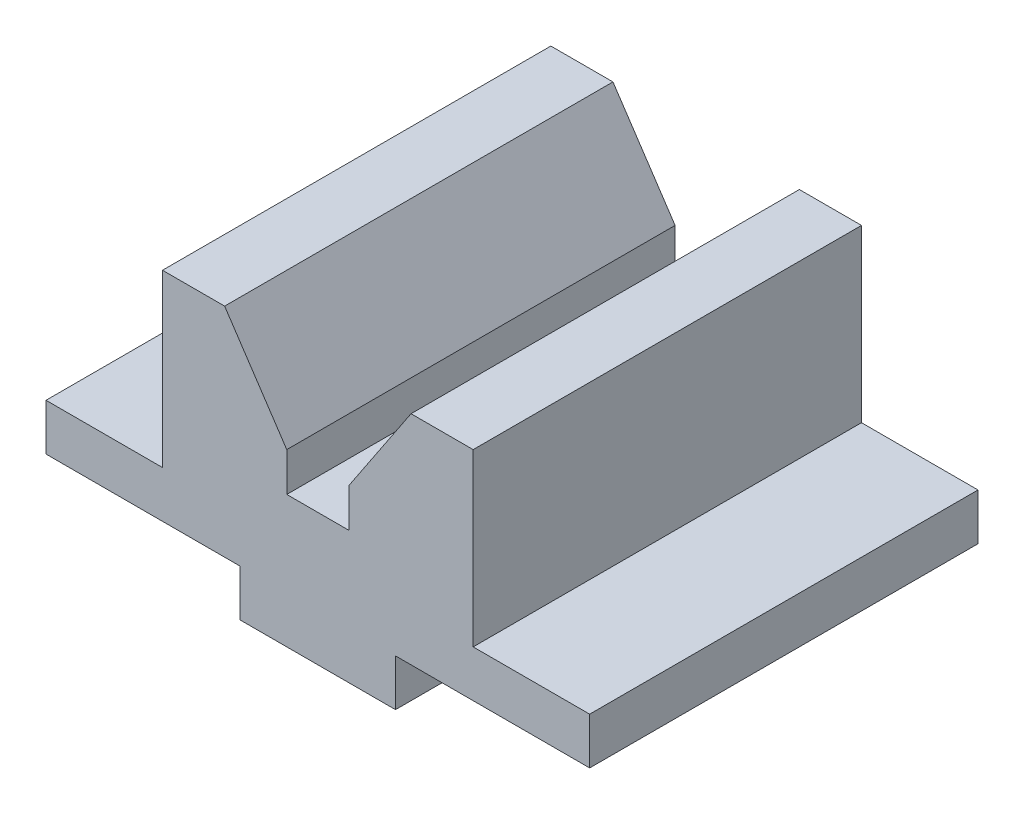
SolidWorks part; units mm, degrees
ref_plane "Front Plane" through (0, 0, 0) normal (0, 0, 1) x (1, 0, 0)
ref_plane "Top Plane" through (0, 0, 0) normal (0, 1, 0) x (1, 0, 0)
ref_plane "Right Plane" through (0, 0, 0) normal (1, 0, 0) x (0, 0, -1)
sketch "Sketch1" plane through (0, 0, 0) normal (0, 0, 1) x (1, 0, 0)
  line L0 (0, 0) -> (0, 17035.5635) construction
  line L1 (0, 0) -> (-17035.5635, 0) construction
  line L2 (10, -6) -> (-10, -6)
  line L3 (-10, -6) -> (-10, 0)
  line L4 (-10, 0) -> (-35, 0)
  line L5 (-35, 0) -> (-35, 6)
  line L6 (-35, 6) -> (-20, 6)
  line L7 (-20, 6) -> (-20, 28)
  line L8 (-20, 28) -> (-12, 28)
  line L9 (-12, 28) -> (-4, 16)
  line L10 (-4, 16) -> (-4, 11)
  line L11 (-4, 11) -> (4, 11)
  line L12 (4, 16) -> (4, 11)
  line L13 (12, 28) -> (4, 16)
  line L14 (20, 28) -> (12, 28)
  line L15 (20, 6) -> (20, 28)
  line L16 (35, 6) -> (20, 6)
  line L17 (35, 0) -> (35, 6)
  line L18 (10, 0) -> (35, 0)
  line L19 (10, -6) -> (10, 0)
  point P17 (0, 11)
  point P25 (0, -6)
  dimension "D1" = 4
  dimension "10" = 10
  dimension "D2" = 12
  dimension "D3" = 8
  dimension "D4" = 34
  dimension "D5" = 6
  dimension "D6" = 15
  dimension "D7" = 6
  dimension "D8" = 70
  dimension "D9" = 5
extrude "Boss-Extrude1" add sketch "Sketch1" along normal blind 50
